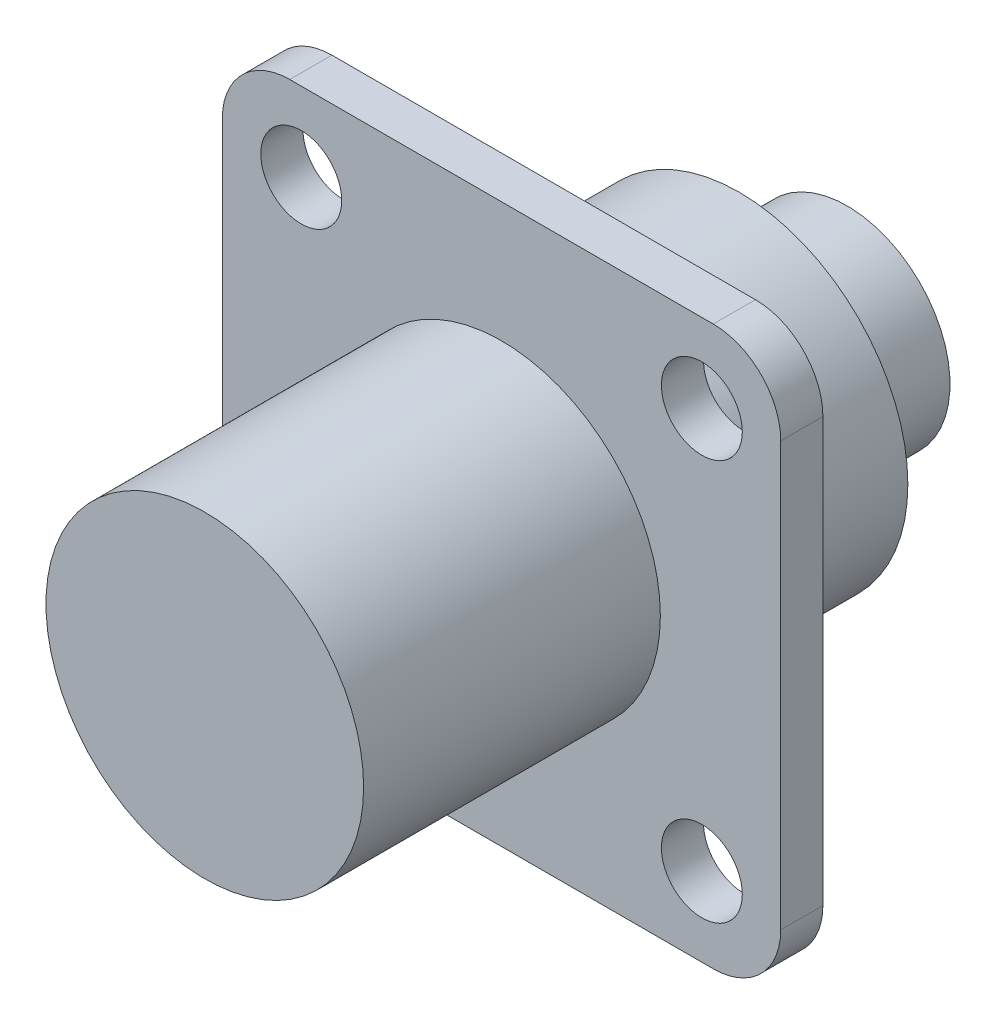
SolidWorks part; units mm, degrees
material "6061-T6 (SS)"
ref_plane "Front Plane" through (0, 0, 0) normal (0, 0, 1) x (1, 0, 0)
ref_plane "Top Plane" through (0, 0, 0) normal (0, 1, 0) x (1, 0, 0)
ref_plane "Right Plane" through (0, 0, 0) normal (1, 0, 0) x (0, 0, -1)
sketch "Sketch1" plane through (0, 0, 0) normal (0, 0, 1) x (1, 0, 0)
  line L1 (-10.5156, 10.5156) -> (10.5156, 10.5156)
  line L2 (-10.5156, 10.5156) -> (-10.5156, -10.5156)
  line L3 (-10.5156, -10.5156) -> (10.5156, -10.5156)
  line L4 (10.5156, 10.5156) -> (10.5156, -10.5156)
  line L5 (-10.5156, 10.5156) -> (10.5156, -10.5156) construction
  line L6 (-10.5156, -10.5156) -> (10.5156, 10.5156) construction
  point P0 (0, 0)
  dimension "D1" = 21.0312
extrude "Boss-Extrude1" add sketch "Sketch1" along normal blind 1.5875
sketch "Sketch2" plane through (0, 0, 1.5875) normal (0, 0, 1) x (1, 0, 0)
  line L1 (-7.5438, 7.5438) -> (7.5438, 7.5438) construction
  line L2 (-7.5438, 7.5438) -> (-7.5438, -7.5438) construction
  line L3 (-7.5438, -7.5438) -> (7.5438, -7.5438) construction
  line L4 (7.5438, 7.5438) -> (7.5438, -7.5438) construction
  line L5 (-7.5438, 7.5438) -> (7.5438, -7.5438) construction
  line L6 (-7.5438, -7.5438) -> (7.5438, 7.5438) construction
  circle A0 centre (-7.5438, 7.5438) radius 1.524
  circle A1 centre (-7.5438, -7.5438) radius 1.524
  circle A2 centre (7.5438, -7.5438) radius 1.524
  circle A3 centre (7.5438, 7.5438) radius 1.524
  point P0 (0, 0)
  dimension "D2" = 3.048
  dimension "D1" = 15.0876
extrude "Cut-Extrude1" cut sketch "Sketch2" against normal through all
fillet "Fillet1" radius 2.54 4 edges at (10.5156, 10.5156, 0.7937) (10.5156, -10.5156, 0.7937) (-10.5156, -10.5156, 0.7937) (-10.5156, 10.5156, 0.7937)
sketch "Sketch3" plane through (0, 0, 1.5875) normal (0, 0, 1) x (1, 0, 0)
  circle A0 centre (0, 0) radius 5.9817
  dimension "D1" = 11.9634
extrude "Boss-Extrude2" add sketch "Sketch3" along normal blind 11.176
sketch "Sketch4" plane through (0, 0, 0) normal (0, 0, -1) x (-1, 0, 0)
  circle A0 centre (0, 0) radius 6.35
  dimension "D1" = 12.7
extrude "Boss-Extrude3" add sketch "Sketch4" along normal blind 7.366
sketch "Sketch5" plane through (0, 0, -7.366) normal (0, 0, -1) x (-1, 0, 0)
  circle A0 centre (0, 0) radius 3.8735
  dimension "D1" = 7.747
extrude "Boss-Extrude4" add sketch "Sketch5" along normal blind 4.064
